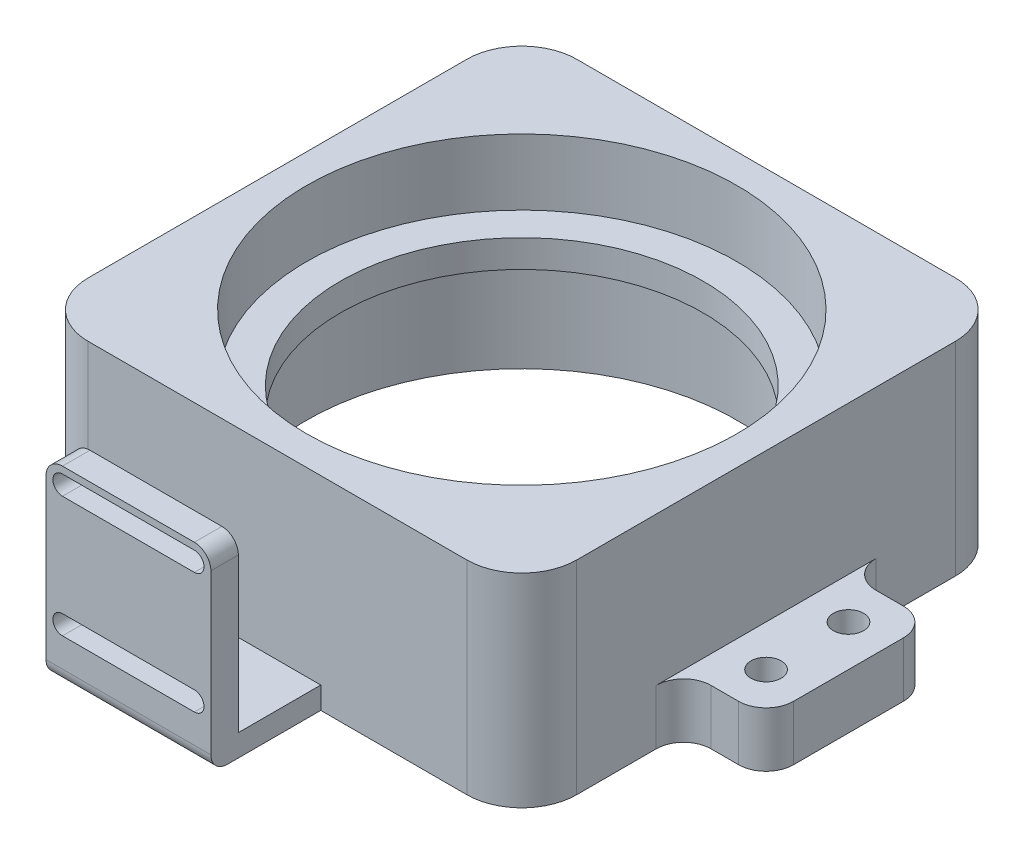
SolidWorks part; units mm, degrees
ref_plane "Front Plane" through (0, 0, 0) normal (0, 0, 1) x (1, 0, 0)
ref_plane "Top Plane" through (0, 0, 0) normal (0, 1, 0) x (1, 0, 0)
ref_plane "Right Plane" through (0, 0, 0) normal (1, 0, 0) x (0, 0, -1)
sketch "Sketch1" plane through (0, 0, 0) normal (0, 1, 0) x (1, 0, 0)
  line L1 (0, 0) -> (88.9, 0)
  line L2 (0, 0) -> (0, 88.9)
  line L3 (0, 88.9) -> (88.9, 88.9)
  line L4 (88.9, 0) -> (88.9, 88.9)
  circle A0 centre (44.45, 44.45) radius 29.88
  circle A1 centre (44.45, 44.45) radius 39.15
  dimension "D1" = 88.9
  dimension "D2" = 88.9
extrude "Boss-Extrude1" add sketch "Sketch1" along normal blind 20 contours L1 L4 L3 L2 A1
sketch "Sketch2" plane through (0, 20, 0) normal (0, 1, 0) x (1, 0, 0)
  line L1 (0, 88.9) -> (88.9, 88.9)
  line L2 (0, 88.9) -> (0, 0)
  line L3 (0, 0) -> (88.9, 0)
  line L4 (88.9, 88.9) -> (88.9, 0)
  circle A0 centre (44.45, 44.45) radius 33
extrude "Boss-Extrude3" add sketch "Sketch2" along normal blind 5
sketch "Sketch3" plane through (0, 25, 0) normal (0, 1, 0) x (1, 0, 0)
  line L1 (0, 0) -> (88.9, 0)
  line L2 (0, 0) -> (0, 88.9)
  line L3 (0, 88.9) -> (88.9, 88.9)
  line L4 (88.9, 0) -> (88.9, 88.9)
  circle A0 centre (44.45, 44.45) radius 39.15
extrude "Boss-Extrude4" add sketch "Sketch3" along normal blind 12
sketch "Sketch4" plane through (0, 0, 0) normal (0, -1, 0) x (1, 0, 0)
  line L0 (0, 0) -> (0, -88.9) construction
  line L1 (0, -44.45) -> (-15, -44.45)
  line L2 (0, -44.45) -> (0, -29.45)
  line L3 (0, -29.45) -> (-15, -29.45)
  line L4 (-15, -44.45) -> (-15, -29.45)
  line L5 (88.9, 0) -> (88.9, -88.9) construction
  line L6 (0, -44.45) -> (-15, -44.45)
  line L7 (0, -44.45) -> (0, -59.45)
  line L8 (0, -59.45) -> (-15, -59.45)
  line L9 (-15, -44.45) -> (-15, -59.45)
  line L10 (88.9, -44.45) -> (103.9, -44.45)
  line L11 (88.9, -44.45) -> (88.9, -29.45)
  line L12 (88.9, -29.45) -> (103.9, -29.45)
  line L13 (103.9, -44.45) -> (103.9, -29.45)
  line L15 (88.9, -44.45) -> (103.9, -44.45)
  line L16 (88.9, -44.45) -> (88.9, -59.45)
  line L17 (88.9, -59.45) -> (103.9, -59.45)
  line L18 (103.9, -44.45) -> (103.9, -59.45)
  circle A0 centre (-7.5, -36.95) radius 2.75
  circle A1 centre (-7.5, -51.95) radius 2.75
  circle A2 centre (96.4, -36.95) radius 2.75
  circle A3 centre (96.4, -51.95) radius 2.75
  line M10 (0, 0) -> (0, -88.9)
  line M12 (88.9, -88.9) -> (88.9, 0)
  dimension "D1" = 15
  dimension "D2" = 15
  dimension "D3" = 15
  dimension "D4" = 15
  dimension "D5" = 15
  dimension "D6" = 15
  dimension "D7" = 15
extrude "Boss-Extrude5" add sketch "Sketch4" against normal blind 10 contours L4 L1 L3 A0 M10 | L1 L9 L8 A1 M10 | L10 L13 L12 A2 M12 | L18 L10 L17 A3 M12
fillet "Fillet1" radius 5 8 edges at (88.9, 5, -59.45) (103.9, 5, -59.45) (103.9, 5, -29.45) (88.9, 5, -29.45) (-15, 5, -59.45) (0, 5, -59.45) (-15, 5, -29.45) (0, 5, -29.45)
fillet "Fillet2" radius 10 4 edges at (0, 18.5, 0) (88.9, 18.5, 0) (88.9, 18.5, -88.9) (0, 18.5, -88.9)
sketch "Sketch5" plane through (0, 0, 0) normal (0, 0, 1) x (1, 0, 0)
  line L0 (10, 0) -> (78.9, 0) construction
  line L1 (52.325, 0) -> (22.325, 0)
  line L2 (52.325, 0) -> (52.325, 4)
  line L3 (52.325, 4) -> (22.325, 4)
  line L4 (22.325, 0) -> (22.325, 4)
  dimension "D1" = 4
  dimension "D2" = 30
extrude "Boss-Extrude6" add sketch "Sketch5" along normal blind 15
sketch "Sketch6" plane through (0, 0, 15) normal (0, 0, 1) x (1, 0, 0)
  line L1 (22.325, 0) -> (52.325, 0)
  line L2 (22.325, 0) -> (22.325, 35)
  line L3 (22.325, 35) -> (52.325, 35)
  line L4 (52.325, 0) -> (52.325, 35)
  line L6 (25.325, 33.75) -> (49.325, 33.75)
  line L7 (25.325, 30.25) -> (49.325, 30.25)
  line L8 (25.325, 11.75) -> (49.325, 11.75)
  line L9 (49.325, 8.25) -> (25.325, 8.25)
  circle A1 centre (25.325, 32) radius 1.75
  circle A2 centre (49.325, 32) radius 1.75
  circle A3 centre (25.325, 10) radius 1.75
  circle A4 centre (49.325, 10) radius 1.75
  line M1 (52.325, 0) -> (52.325, 4)
  line M2 (52.325, 4) -> (22.325, 4)
  line M3 (22.325, 4) -> (22.325, 0)
  line M4 (22.325, 0) -> (52.325, 0)
  dimension "D2" = 3
  dimension "D4" = 3
  dimension "D6" = 22
  dimension "D7" = 3
  dimension "D1" = 35
  dimension "D3" = 3
  dimension "D5" = 3
  dimension "D8" = 3
extrude "Boss-Extrude7" add sketch "Sketch6" along normal blind 5 contours L4 L3 L2 A4 L9 A3 L8 A2 L7 A1 L6 M2 | M4 M1 M2 M3
fillet "Fillet3" radius 3 3 edges at (37.325, 0, 20) (22.325, 35, 17.5) (52.325, 35, 17.5)
